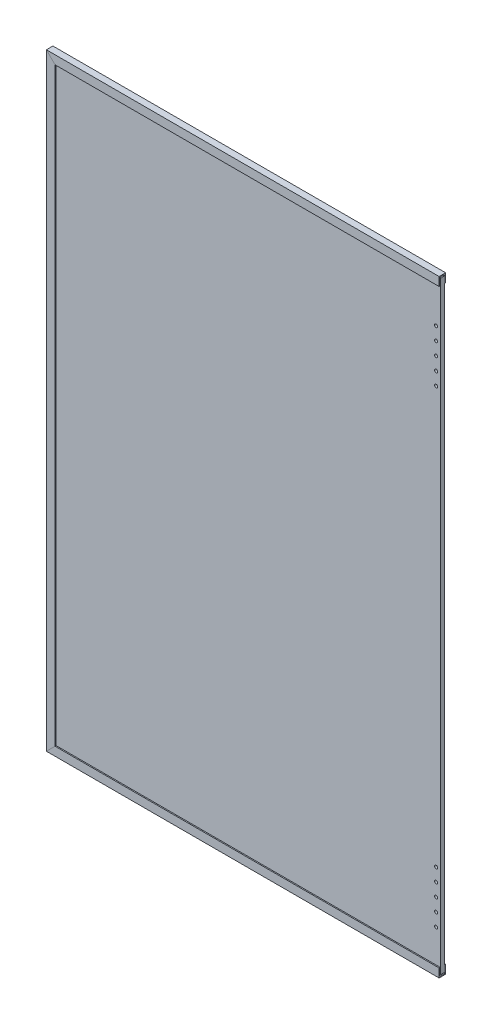
SolidWorks part; units mm, degrees
material "PC High Viscosity"
ref_plane "Front Plane" through (0, 0, 0) normal (0, 0, 1) x (1, 0, 0)
ref_plane "Top Plane" through (0, 0, 0) normal (0, 1, 0) x (1, 0, 0)
ref_plane "Right Plane" through (0, 0, 0) normal (1, 0, 0) x (0, 0, -1)
sketch "Shelf opening" plane through (0, 0, 0) normal (0, 0, 1) x (1, 0, 0)
  line L1 (0, 0) -> (577.85, 0)
  line L2 (0, 0) -> (0, 863.6)
  line L3 (0, 863.6) -> (577.85, 863.6)
  line L4 (577.85, 0) -> (577.85, 863.6)
  dimension "D1" = 577.85
  dimension "D2" = 863.6
sketch "Sketch2" plane through (0, 0, 0) normal (0, 0, 1) x (1, 0, 0)
  line L0 (577.85, 0) -> (577.85, 863.6) construction
  line L1 (3.175, 876.3) -> (577.85, 876.3)
  line L2 (3.175, 876.3) -> (3.175, -12.7)
  line L3 (3.175, -12.7) -> (577.85, -12.7)
  line L4 (577.85, 876.3) -> (577.85, -12.7)
  line L5 (0, 863.6) -> (577.85, 863.6) construction
  line L6 (0, 0) -> (0, 863.6) construction
  line L7 (0, 0) -> (577.85, 0) construction
  dimension "D1" = 12.7
  dimension "D2" = 3.175
  dimension "D3" = 12.7
extrude "Frame outer dimensions" add sketch "Sketch2" along normal mid plane 9.525
sketch "Sketch3" plane through (0, 0, 4.7625) normal (0, 0, 1) x (1, 0, 0)
  line L0 (577.85, -12.7) -> (577.85, 876.3) construction
  line L1 (577.85, 863.6) -> (15.875, 863.6)
  line L2 (577.85, 863.6) -> (577.85, 0)
  line L3 (577.85, 0) -> (15.875, 0)
  line L4 (15.875, 863.6) -> (15.875, 0)
  line L5 (577.85, 876.3) -> (3.175, 876.3) construction
  line L6 (3.175, 876.3) -> (3.175, -12.7) construction
  line L7 (3.175, -12.7) -> (577.85, -12.7) construction
  dimension "D1" = 12.7
  dimension "D2" = 12.7
  dimension "D3" = 12.7
extrude "Frame inner dimensions" cut sketch "Sketch3" against normal through all
sketch "Sketch4" plane through (0, 0, 0) normal (0, 0, 1) x (1, 0, 0)
  line L0 (577.85, 863.6) -> (577.85, 876.3) construction
  line L1 (577.85, 874.7125) -> (4.7625, 874.7125)
  line L2 (577.85, 874.7125) -> (577.85, -11.1125)
  line L3 (577.85, -11.1125) -> (4.7625, -11.1125)
  line L4 (4.7625, 874.7125) -> (4.7625, -11.1125)
  line L5 (577.85, 876.3) -> (3.175, 876.3) construction
  line L6 (3.175, 876.3) -> (3.175, -12.7) construction
  line L7 (3.175, -12.7) -> (577.85, -12.7) construction
  dimension "D1" = 1.5875
  dimension "D2" = 1.5875
  dimension "D3" = 1.5875
extrude "Frame profile" cut sketch "Sketch4" along normal offset from surface 1.5875 and the other way offset from surface (3.175 mm away) 1.5875 up to face at (293.6875, 431.8, 4.7625) other way up to face at (293.6875, 431.8, -4.7625)
sketch "Frame sections" plane through (0, 0, 4.7625) normal (0, 0, 1) x (1, 0, 0)
  line L0 (3.175, 876.3) -> (15.875, 863.6)
  line L1 (3.175, -12.7) -> (15.875, 0)
split "Frame section split" trim tools "Frame sections" bodies to split 103 resulting bodies 105 106 107
sketch "Sketch5" plane through (0, 0, 0) normal (0, 0, 1) x (1, 0, 0)
  line L0 (577.85, 863.6) -> (577.85, 876.3) construction
  line L1 (577.85, 873.125) -> (6.35, 873.125)
  line L2 (577.85, 873.125) -> (577.85, -9.525)
  line L3 (577.85, -9.525) -> (6.35, -9.525)
  line L4 (6.35, 873.125) -> (6.35, -9.525)
  line L5 (4.7625, 874.7125) -> (577.85, 874.7125) construction
  line L6 (4.7625, -11.1125) -> (4.7625, 874.7125) construction
  line L7 (577.85, -11.1125) -> (4.7625, -11.1125) construction
  dimension "D1" = 1.5875
  dimension "D2" = 1.5875
  dimension "D3" = 1.5875
  dimension "D4" = 571.5
  dimension "D5" = 882.65
extrude "Door panel" add sketch "Sketch5" along normal mid plane 5.588 separate body
sketch "Hinge positions" plane through (0, 0, 2.794) normal (0, 0, 1) x (1, 0, 0)
  line L0 (577.85, -9.525) -> (577.85, 873.125) construction
  line L1 (577.85, 819.15) -> (565.15, 819.15)
  line L2 (577.85, 819.15) -> (577.85, 723.9)
  line L3 (577.85, 723.9) -> (565.15, 723.9)
  line L4 (565.15, 819.15) -> (565.15, 723.9)
  line L5 (565.15, 133.35) -> (577.85, 133.35)
  line L6 (565.15, 133.35) -> (565.15, 38.1)
  line L7 (565.15, 38.1) -> (577.85, 38.1)
  line L8 (577.85, 133.35) -> (577.85, 38.1)
  line L10 (0, 0) -> (577.85, 0) construction
  line L11 (0, 863.6) -> (577.85, 863.6) construction
  dimension "D1" = 95.25
  dimension "D2" = 12.7
  dimension "D3" = 38.1
  dimension "D4" = 44.45
  dimension "D5" = 685.8
sketch "Sketch8" plane through (0, 0, 2.794) normal (0, 0, 1) x (1, 0, 0)
  line L0 (565.15, 85.725) -> (577.85, 85.725) construction
  line L2 (565.15, 133.35) -> (565.15, 38.1) construction
  line L3 (577.85, 133.35) -> (577.85, 38.1) construction
  line L4 (565.15, 771.525) -> (577.85, 771.525) construction
  line L6 (565.15, 819.15) -> (565.15, 723.9) construction
  line L7 (577.85, 819.15) -> (577.85, 723.9) construction
  point P0 (571.5, 47.625)
  point P11 (571.5, 66.675)
  point P12 (571.5, 85.725)
  point P13 (571.5, 104.775)
  point P14 (571.5, 123.825)
  point P15 (571.5, 752.475)
  point P16 (571.5, 771.525)
  point P17 (571.5, 790.575)
  point P18 (571.5, 809.625)
  point P19 (571.5, 733.425)
  point P35 (572.1856, 752.475)
  point P36 (0, 0)
  dimension "D3" = 19.05
  dimension "D1" = 5
  dimension "D2" = 2
hole_wizard "#8 Clearance Hole1" positions "Sketch8" profile "Sketch9" hole size "#8" standard "ANSI Inch" end condition through all
sketch "Sketch9" plane through (571.5, 47.625, 2.794) normal (1, 0, 0) x (0, -1, 0)
  line L0 (0, 0) -> (0, 7.5565)
  line L1 (0, 7.5565) -> (2.2479, 7.5565)
  line L2 (2.2479, 7.5565) -> (2.2479, 0)
  line L5 (2.2479, 0) -> (0, 0)
  line L11 (0, -6.35) -> (0, 107.95) construction
  dimension "Thru Hole Dia." = 4.4958
  dimension "Thru Hole Depth" = 7.5565
